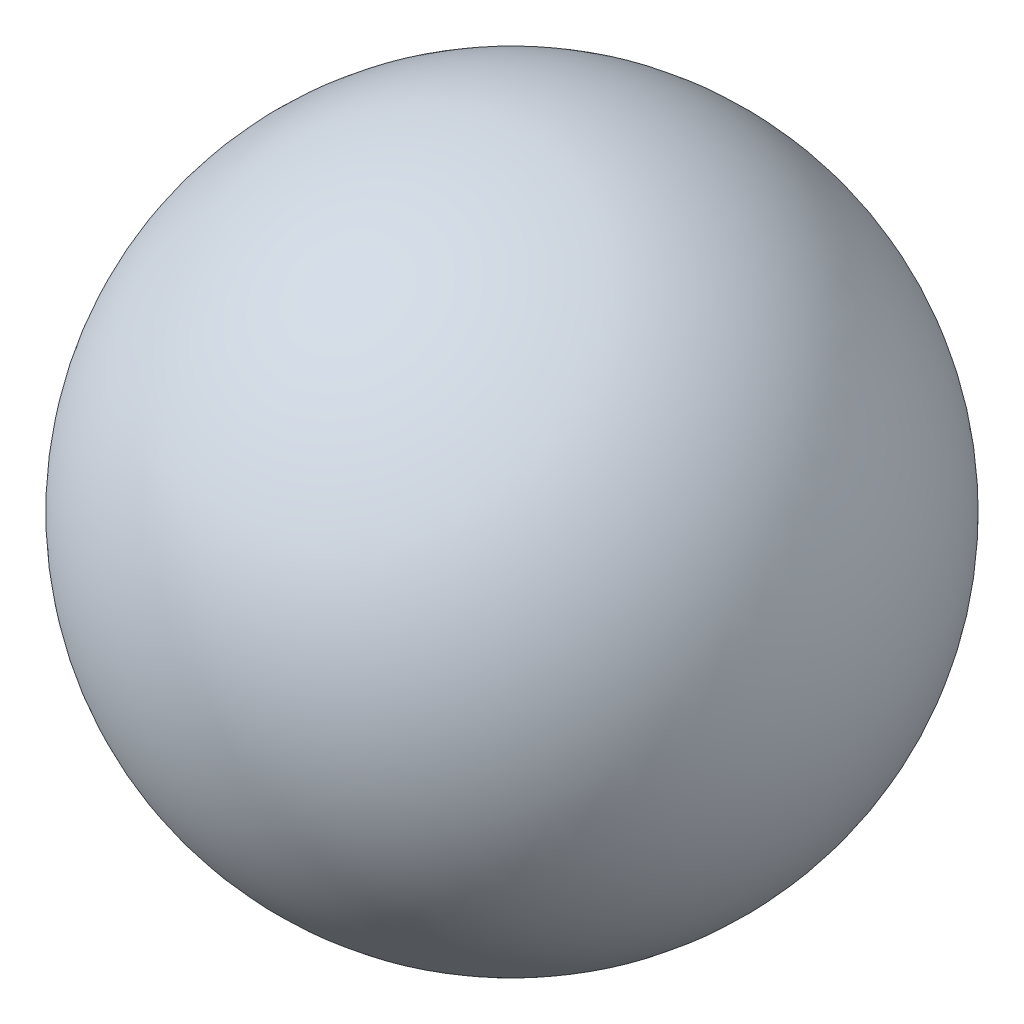
SolidWorks part; units mm, degrees
material "ABS"
ref_plane "Front Plane" through (0, 0, 0) normal (0, 0, 1) x (1, 0, 0)
ref_plane "Top Plane" through (0, 0, 0) normal (0, 1, 0) x (1, 0, 0)
ref_plane "Right Plane" through (0, 0, 0) normal (1, 0, 0) x (0, 0, -1)
sketch "Sketch1" plane through (0, 0, 0) normal (0, 0, 1) x (1, 0, 0)
  line L0 (0, 0) -> (0, 50)
  arc A0 (0, 50) -> (0, 0) centre (0, 25) cw
  dimension "D1" = 50
revolve "Revolve1" add sketch "Sketch1" angle 360 about L0
sketch3d "URDF Reference"
  line L0 (0, 0, 0) -> (10, 0, 0) construction
  line L1 (0, 0, 0) -> (0, 0, -10) construction
  point P0 (0, 0, 0)
  point P1 (0, 0, 0)
